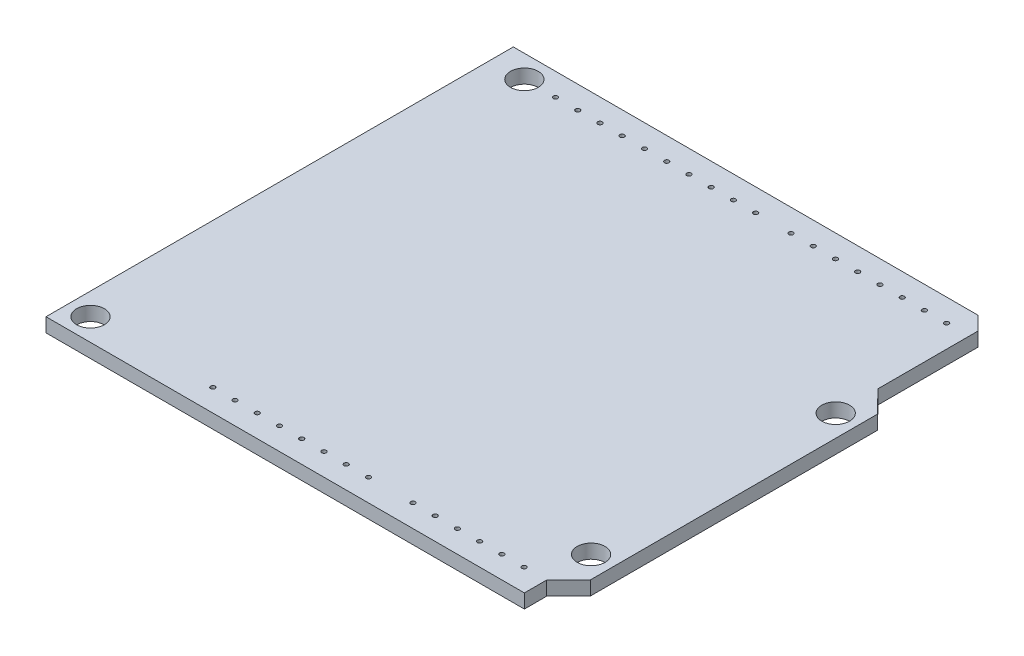
SolidWorks part; units mm, degrees
ref_plane "Alzado" through (0, 0, 0) normal (0, 0, 1) x (1, 0, 0)
ref_plane "Planta" through (0, 0, 0) normal (0, 1, 0) x (1, 0, 0)
ref_plane "Vista lateral" through (0, 0, 0) normal (1, 0, 0) x (0, 0, -1)
sketch "Board" plane through (0, 0, 0) normal (0, 1, 0) x (1, 0, 0)
  line L0 (57.12, 37.846) -> (57.12, 5.08)
  line L1 (54.64, 0) -> (0, 0)
  line L2 (54.64, 51.8137) -> (54.64, 40.386)
  line L3 (54.64, 0) -> (54.64, 2.54)
  line L4 (54.64, 40.386) -> (57.12, 37.846)
  line L5 (57.12, 5.08) -> (54.64, 2.54)
  line L6 (0, 0) -> (0, 53.3785)
  line L7 (53.0752, 53.3785) -> (0, 53.3785)
  line L8 (54.64, 51.8137) -> (53.0752, 53.3785)
sketch "Drills" plane through (0, 0, 0) normal (0, 1, 0) x (1, 0, 0)
  line L0 (2.54, 2.54) -> (52.07, 2.54) construction
  line L2 (3.84, 50.8) -> (52.07, 50.8) construction
  circle A0 centre (3.84, 50.8) radius 1.5875
  circle A1 centre (54.64, 35.56) radius 1.5875
  circle A2 centre (54.64, 7.62) radius 1.5875
  circle A3 centre (2.54, 2.54) radius 1.5875
sketch "Pinout" plane through (0, 0, 0) normal (0, 1, 0) x (1, 0, 0)
  circle A0 centre (52.07, 2.54) radius 0.254
  circle A1 centre (49.53, 2.54) radius 0.254
  circle A2 centre (46.99, 2.54) radius 0.254
  circle A3 centre (44.45, 2.54) radius 0.254
  circle A4 centre (41.91, 2.54) radius 0.254
  circle A5 centre (39.37, 2.54) radius 0.254
  circle A6 centre (34.29, 2.54) radius 0.254
  circle A7 centre (31.75, 2.54) radius 0.254
  circle A8 centre (29.21, 2.54) radius 0.254
  circle A9 centre (26.67, 2.54) radius 0.254
  circle A10 centre (24.13, 2.54) radius 0.254
  circle A11 centre (21.59, 2.54) radius 0.254
  circle A12 centre (19.05, 2.54) radius 0.254
  circle A13 centre (16.51, 2.54) radius 0.254
  circle A14 centre (52.07, 50.8) radius 0.254
  circle A15 centre (49.53, 50.8) radius 0.254
  circle A16 centre (46.99, 50.8) radius 0.254
  circle A17 centre (44.45, 50.8) radius 0.254
  circle A18 centre (41.91, 50.8) radius 0.254
  circle A19 centre (39.37, 50.8) radius 0.254
  circle A20 centre (36.83, 50.8) radius 0.254
  circle A21 centre (34.29, 50.8) radius 0.254
  circle A22 centre (30.256, 50.8) radius 0.254
  circle A23 centre (27.716, 50.8) radius 0.254
  circle A24 centre (25.176, 50.8) radius 0.254
  circle A25 centre (22.636, 50.8) radius 0.254
  circle A26 centre (20.096, 50.8) radius 0.254
  circle A27 centre (17.556, 50.8) radius 0.254
  circle A28 centre (15.016, 50.8) radius 0.254
  circle A29 centre (12.476, 50.8) radius 0.254
  circle A30 centre (9.936, 50.8) radius 0.254
  circle A31 centre (7.396, 50.8) radius 0.254
  dimension "D1" = 8
  dimension "D2" = 10
  dimension "D3" = 6
  dimension "D4" = 8
extrude "Saliente-Extruir1" add sketch "Board" along normal blind 1.6002
extrude "Cortar-Extruir2" cut sketch "Pinout" along normal blind 1.6002
extrude "Cortar-Extruir3" cut sketch "Drills" along normal blind 1.6002
